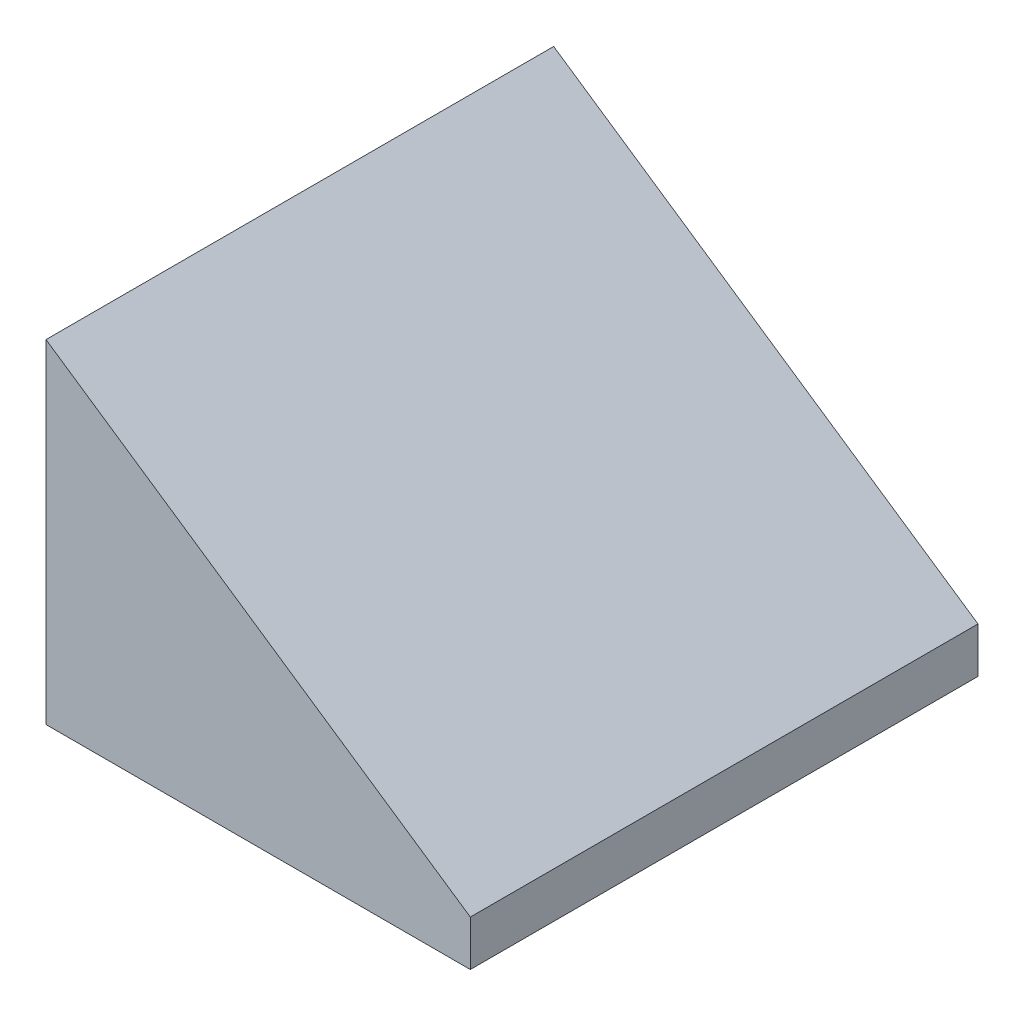
SolidWorks part; units mm, degrees
ref_plane "Front Plane" through (0, 0, 0) normal (0, 0, 1) x (1, 0, 0)
ref_plane "Top Plane" through (0, 0, 0) normal (0, 1, 0) x (1, 0, 0)
ref_plane "Right Plane" through (0, 0, 0) normal (1, 0, 0) x (0, 0, -1)
sketch "Sketch1" plane through (0, 0, 0) normal (0, 1, 0) x (1, 0, 0)
  line L1 (14, -16.75) -> (-14, -16.75)
  line L2 (14, -16.75) -> (14, 16.75)
  line L3 (14, 16.75) -> (-14, 16.75)
  line L4 (-14, -16.75) -> (-14, 16.75)
  line L5 (14, -16.75) -> (-14, 16.75) construction
  line L6 (14, 16.75) -> (-14, -16.75) construction
  point P0 (0, 0)
  dimension "D1" = 33.5
  dimension "D2" = 28
extrude "Boss-Extrude1" add sketch "Sketch1" along normal blind 22
sketch "Sketch3" plane through (0, 0, 16.75) normal (0, 0, 1) x (1, 0, 0)
  line L0 (-14, 22) -> (14, 3)
  line L1 (14, 22) -> (14, 0) construction
  line L3 (-14, 22) -> (14, 22)
  line L4 (-14, 22) -> (-14, 3)
  line L5 (-14, 3) -> (14, 3)
  line L6 (14, 22) -> (14, 3)
  line M6 (14, 0) -> (14, 22)
  line M7 (14, 22) -> (-14, 22)
  dimension "D1" = 3
extrude "Cut-Extrude1" cut sketch "Sketch3" against normal blind 44 contours L0 M7 M6
